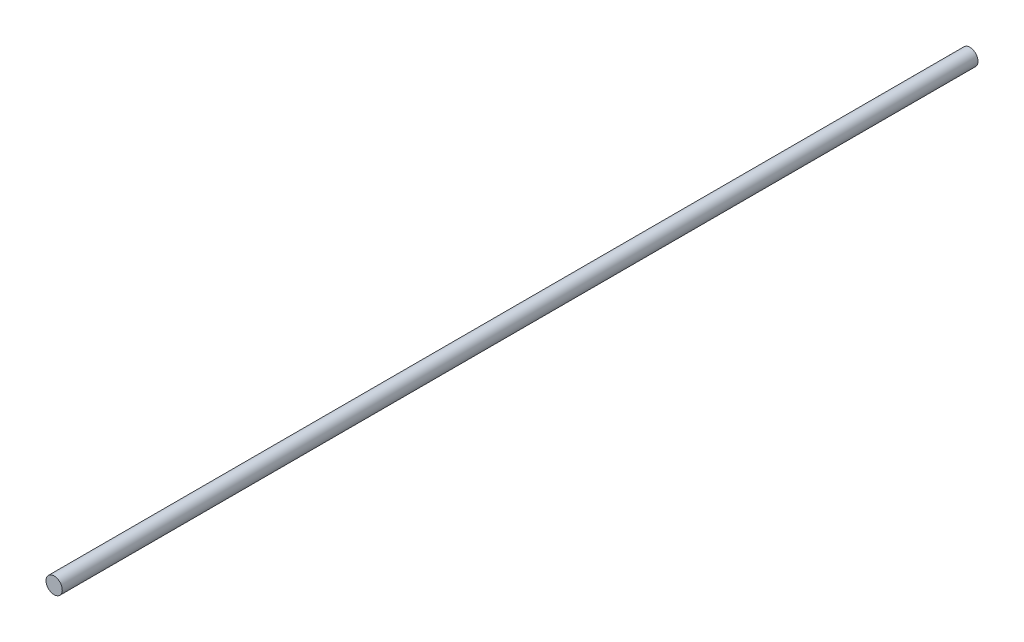
SolidWorks part; units mm, degrees
material "合金钢"
ref_plane "前视基准面" through (0, 0, 0) normal (0, 0, 1) x (1, 0, 0)
ref_plane "上视基准面" through (0, 0, 0) normal (0, 1, 0) x (1, 0, 0)
ref_plane "右视基准面" through (0, 0, 0) normal (1, 0, 0) x (0, 0, -1)
sketch "草图1" plane through (0, 0, 0) normal (0, 0, 1) x (1, 0, 0)
  circle A0 centre (0, 0) radius 4
  dimension "D1" = 8
extrude "凸台-拉伸1" add sketch "草图1" along normal blind 450
sketch "草图2" plane through (0, 0, 450) normal (0, 0, 1) x (1, 0, 0)
  point P0 (0, 0)
sketch "草图3" plane through (0, 0, 0) normal (0, 0, -1) x (-1, 0, 0)
  point P0 (0, 0)
